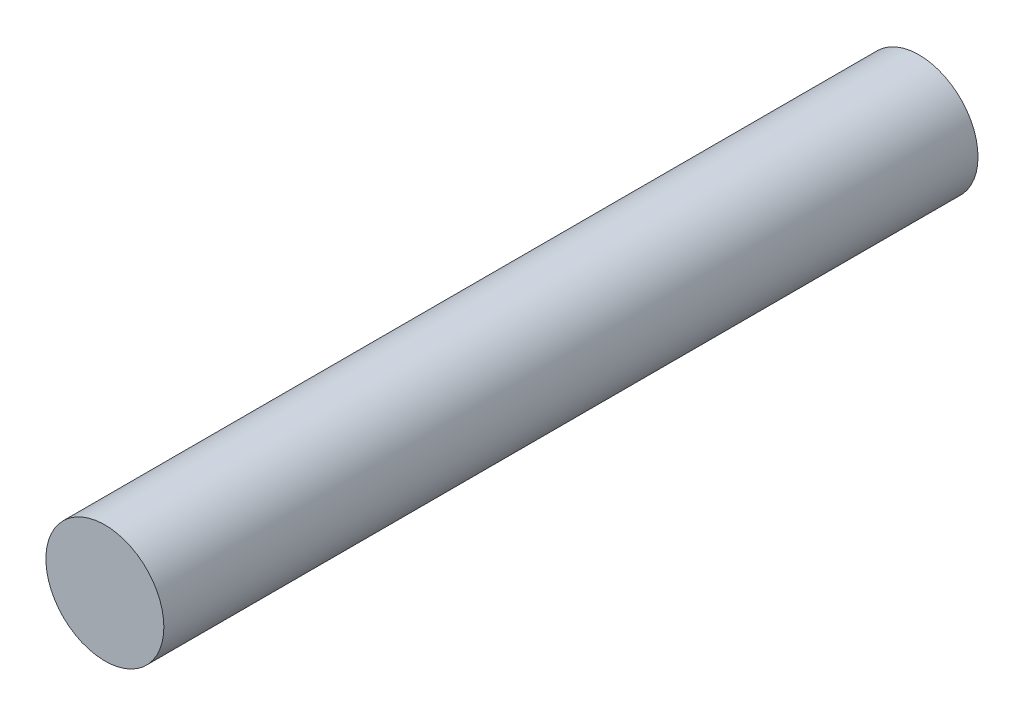
SolidWorks part; units mm, degrees
ref_plane "Front Plane" through (0, 0, 0) normal (0, 0, 1) x (1, 0, 0)
ref_plane "Top Plane" through (0, 0, 0) normal (0, 1, 0) x (1, 0, 0)
ref_plane "Right Plane" through (0, 0, 0) normal (1, 0, 0) x (0, 0, -1)
sketch "Sketch2" plane through (0, 0, 0) normal (0, 0, 1) x (1, 0, 0)
  circle A0 centre (0, 0) radius 50.8
  dimension "D1" = 101.6
extrude "Boss-Extrude1" add sketch "Sketch2" along normal blind 701.2
